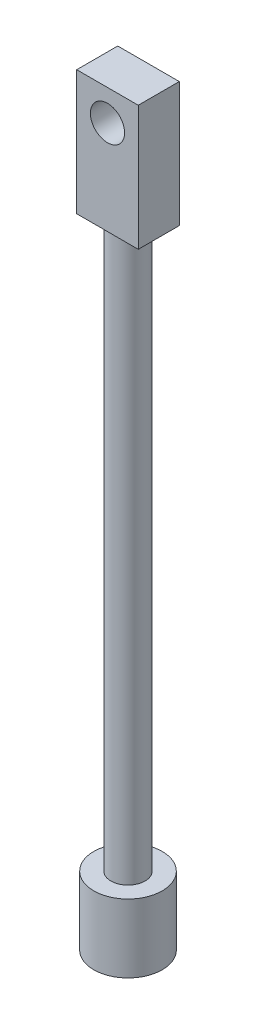
SolidWorks part; units mm, degrees
ref_plane "Plan1" through (0, 0, 0) normal (0, 0, 1) x (1, 0, 0)
ref_plane "Plan2" through (0, 0, 0) normal (0, 1, 0) x (1, 0, 0)
ref_plane "Plan3" through (0, 0, 0) normal (1, 0, 0) x (0, 0, -1)
sketch "Esquisse1" plane through (0, 0, 0) normal (0, 0, 1) x (1, 0, 0)
  line L0 (0, -40) -> (0, 110) construction
  line L1 (0, 0) -> (5, 0)
  line L2 (5, 0) -> (5, 165)
  line L3 (5, 165) -> (0, 165)
  line L4 (0, 165) -> (0, 0)
  dimension "D1" = 5
  dimension "D2" = 165
revolve "Base-Révolution" add sketch "Esquisse1" angle 360 about L0
sketch "Esquisse2" plane through (0, 0, 0) normal (0, 0, 1) x (1, 0, 0)
  line L0 (0, 0) -> (0, -70) construction
  line L1 (0, -40) -> (0, 110) construction
  line L2 (0, -20) -> (10, -20)
  line L3 (10, -20) -> (10, 0)
  line L4 (10, 0) -> (0, 0)
  line L5 (0, 0) -> (0, -20)
  line L6 (-5, 0) -> (5, 0) construction
  dimension "D1" = 10
  dimension "D2" = 20
revolve "Boss.-Révol.1" add sketch "Esquisse2" angle 360 about L0
sketch "Esquisse3" plane through (0, 0, 0) normal (0, 0, 1) x (1, 0, 0)
  line L0 (0, 0) -> (0, 210) construction
  line L1 (-9, 165) -> (9, 165)
  line L2 (9, 165) -> (9, 201.5)
  line L3 (-9, 165) -> (-9, 201.5)
  line L4 (9, 201.5) -> (-9, 201.5)
  line L5 (5, 165) -> (-5, 165) construction
  circle A0 centre (0, 192.5) radius 5
  point P6 (0, 165)
  point P9 (0, 201.5)
  dimension "D4" = 10
  dimension "D1" = 36.5
  dimension "D2" = 9
  dimension "D3" = 9
extrude "Boss.-Extru.1" add sketch "Esquisse3" along normal mid plane 12
